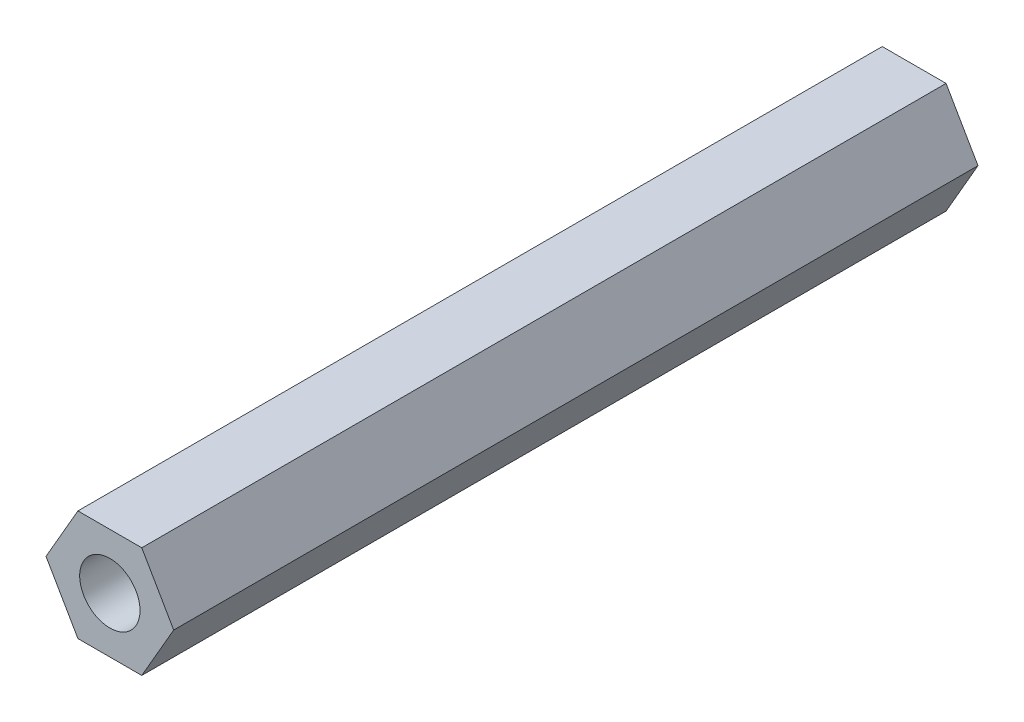
SolidWorks part; units mm, degrees
ref_plane "Спереди" through (0, 0, 0) normal (0, 0, 1) x (1, 0, 0)
ref_plane "Сверху" through (0, 0, 0) normal (0, 1, 0) x (1, 0, 0)
ref_plane "Справа" through (0, 0, 0) normal (1, 0, 0) x (0, 0, -1)
sketch "Эскиз1" plane through (0, 0, 0) normal (0, 0, 1) x (1, 0, 0)
  line L1 (3.1754, 0) -> (1.5877, 2.75)
  line L2 (1.5877, 2.75) -> (-1.5877, 2.75)
  line L3 (-1.5877, 2.75) -> (-3.1754, 0)
  line L4 (-3.1754, 0) -> (-1.5877, -2.75)
  line L5 (-1.5877, -2.75) -> (1.5877, -2.75)
  line L6 (1.5877, -2.75) -> (3.1754, 0)
  circle A0 centre (0, 0) radius 2.75 construction
  circle A1 centre (0, 0) radius 1.5
  dimension "D2" = 3
  dimension "D1" = 5.5
extrude "Бобышка-Вытянуть1" add sketch "Эскиз1" along normal blind 40
